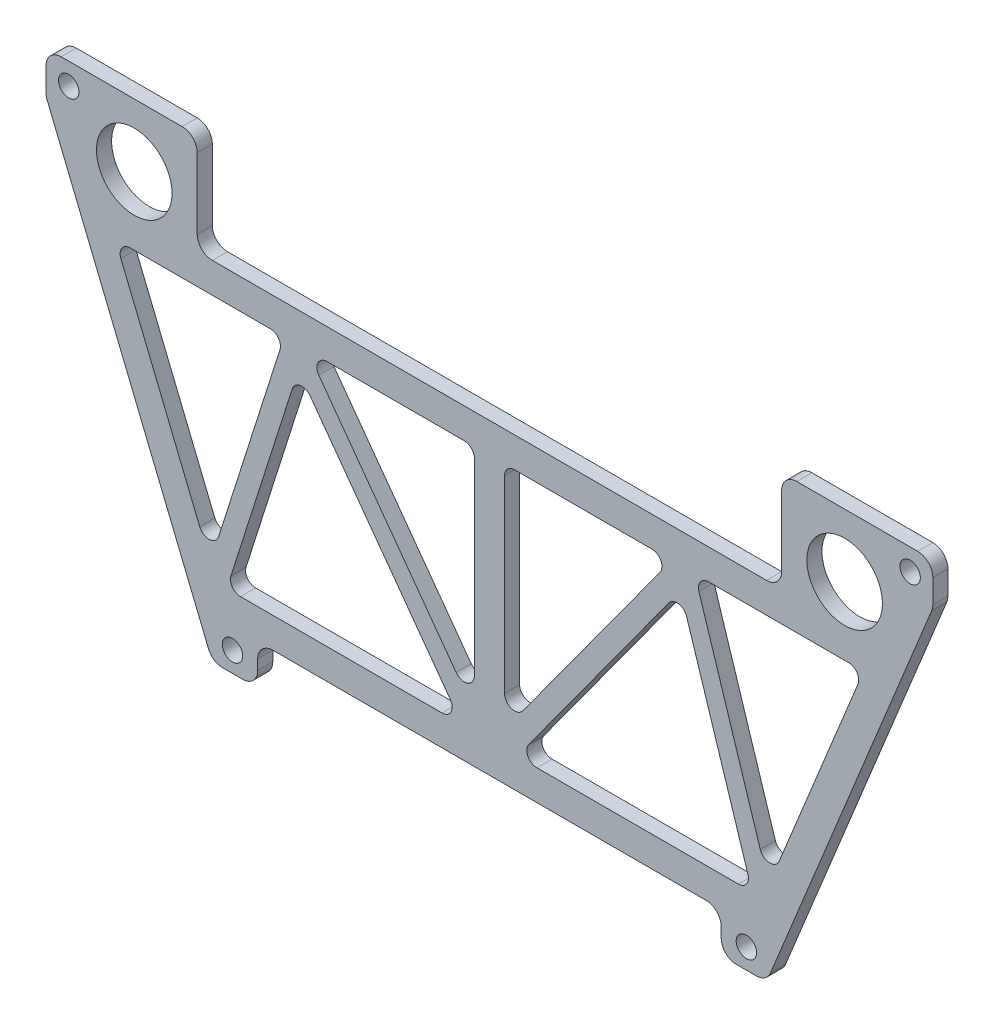
SolidWorks part; units mm, degrees
material "Thornel Mat VMA"
ref_plane "前视基准面" through (0, 0, 0) normal (0, 0, 1) x (1, 0, 0)
ref_plane "上视基准面" through (0, 0, 0) normal (0, 1, 0) x (1, 0, 0)
ref_plane "右视基准面" through (0, 0, 0) normal (1, 0, 0) x (0, 0, -1)
other "Configuration Table"
sketch "草图1" plane through (0, 0, 0) normal (0, 0, 1) x (1, 0, 0)
  line L1 (-88, -44.5) -> (88, -44.5)
  line L2 (-88, -44.5) -> (-88, 44.5)
  line L3 (-88, 44.5) -> (88, 44.5)
  line L4 (88, -44.5) -> (88, 44.5)
  line L5 (-88, -44.5) -> (88, 44.5) construction
  line L6 (-88, 44.5) -> (88, -44.5) construction
  point P0 (0, 0)
  dimension "D1" = 176
  dimension "D2" = 89
extrude "凸台-拉伸1" add sketch "草图1" along normal blind 3
sketch "草图2" plane through (0, 0, 0) normal (0, 0, -1) x (-1, 0, 0)
  circle A0 centre (-83.5, 40.2) radius 2.025 construction
  circle A1 centre (-83.5, 40.2) radius 2.025
  circle A2 centre (83.5, 40.2) radius 2.025 construction
  circle A3 centre (83.5, 40.2) radius 2.025
  circle A4 centre (51, -40.5) radius 2.025 construction
  circle A5 centre (-51, -40.5) radius 2.025 construction
  circle A6 centre (51, -40.5) radius 2.025
  circle A7 centre (-51, -40.5) radius 2.025
extrude "切除-拉伸1" cut sketch "草图2" against normal blind 4
sketch "草图3" plane through (0, 0, 0) normal (0, 0, -1) x (-1, 0, 0)
  line L1 (88, -44.5) -> (88, 36.2)
  line L2 (55, -44.5) -> (88, -44.5)
  line L5 (-88, 36.2) -> (-55, -44.5)
  line L6 (-88, -44.5) -> (-88, 44.5) construction
  line L7 (88, -44.5) -> (-88, -44.5) construction
  line L8 (-55, -44.5) -> (-88, -44.5)
  line L9 (-88, -44.5) -> (-88, 36.2)
  line L10 (0, 0) -> (0, 44.5) construction
  line L11 (-88, 44.5) -> (88, 44.5) construction
  line L12 (88, 36.2) -> (55, -44.5)
  circle A0 centre (-83.5, 40.2) radius 2.025 construction
  circle A1 centre (-51, -40.5) radius 2.025 construction
  dimension "D1" = 4
  dimension "D2" = 4
extrude "切除-拉伸2" cut sketch "草图3" against normal blind 4
sketch "草图4" plane through (0, 0, 0) normal (0, 0, -1) x (-1, 0, 0)
  line L0 (-88, 44.5) -> (88, 44.5) construction
  line L1 (-58, 24.5) -> (58, 24.5)
  line L2 (-58, 24.5) -> (-58, 64.5)
  line L3 (-58, 64.5) -> (58, 64.5)
  line L4 (58, 24.5) -> (58, 64.5)
  line L5 (-58, 24.5) -> (58, 64.5) construction
  line L6 (-58, 64.5) -> (58, 24.5) construction
  line L7 (-88, 36.2) -> (-88, 44.5) construction
  point P0 (0, 44.5)
  dimension "D1" = 30
  dimension "D2" = 20
extrude "切除-拉伸3" cut sketch "草图4" against normal blind 4
sketch "草图5" plane through (0, 0, 0) normal (0, 0, -1) x (-1, 0, 0)
  line L0 (55, -44.5) -> (-55, -44.5) construction
  line L1 (-46, -52.5) -> (46, -52.5)
  line L2 (-46, -52.5) -> (-46, -36.5)
  line L3 (-46, -36.5) -> (46, -36.5)
  line L4 (46, -52.5) -> (46, -36.5)
  line L5 (-46, -52.5) -> (46, -36.5) construction
  line L6 (-46, -36.5) -> (46, -52.5) construction
  circle A0 centre (51, -40.5) radius 2.025 construction
  point P0 (0, -44.5)
  dimension "D1" = 8
  dimension "D2" = 5
extrude "切除-拉伸4" cut sketch "草图5" against normal blind 4
sketch "草图6" plane through (0, 0, 0) normal (0, 0, -1) x (-1, 0, 0)
  line L0 (-74.2798, 18.5) -> (-54.2426, -30.5)
  line L1 (-54.2426, -30.5) -> (54.2426, -30.5)
  line L2 (54.2426, -30.5) -> (74.2798, 18.5)
  line L3 (74.2798, 18.5) -> (-74.2798, 18.5)
  line L4 (-58, 24.5) -> (58, 24.5) construction
  line L5 (-55, -44.5) -> (-88, 36.2) construction
  line L7 (88, 36.2) -> (55, -44.5) construction
  line L8 (46, -36.5) -> (-46, -36.5) construction
  line L9 (0, 18.5) -> (0, -30.5) construction
  line L10 (-3, 18.5) -> (-3, -30.5)
  line L11 (3, 18.5) -> (3, -30.5)
  dimension "D1" = 6
  dimension "D2" = 6
  dimension "D3" = 6
  dimension "D4" = 6
  dimension "D5" = 3
  dimension "D6" = 3
extrude "切除-拉伸5" cut sketch "草图6" against normal blind 24 contours L10 L3 L0 L1 | L3 L11 L1 L2
sketch "草图7" plane through (0, 0, 0) normal (0, 0, -1) x (-1, 0, 0)
  line L0 (-54.2426, -30.5) -> (-38.6399, 18.5) construction
  line L1 (-3, 18.5) -> (-74.2798, 18.5) construction
  line L2 (-38.6399, 18.5) -> (-3, -30.5) construction
  line L3 (3, -30.5) -> (38.6399, 18.5) construction
  line L4 (74.2798, 18.5) -> (3, 18.5) construction
  line L5 (38.6399, 18.5) -> (54.2426, -30.5) construction
  line L6 (-52.3369, -31.1068) -> (-37.9331, 14.1281)
  line L7 (-37.9331, 14.1281) -> (-4.6174, -31.6764)
  line L8 (4.6174, -31.6764) -> (37.9331, 14.1281)
  line L9 (37.9331, 14.1281) -> (52.3369, -31.1068)
  line L10 (-56.1484, -29.8932) -> (-39.3467, 22.8719)
  line L11 (-39.3467, 22.8719) -> (-1.3826, -29.3236)
  line L12 (1.3826, -29.3236) -> (39.3467, 22.8719)
  line L13 (39.3467, 22.8719) -> (56.1484, -29.8932)
  arc A0 (-52.3369, -31.1068) -> (-56.1484, -29.8932) centre (-54.2426, -30.5) cw
  arc A1 (-4.6174, -31.6764) -> (-1.3826, -29.3236) centre (-3, -30.5) ccw
  arc A2 (4.6174, -31.6764) -> (1.3826, -29.3236) centre (3, -30.5) cw
  arc A3 (52.3369, -31.1068) -> (56.1484, -29.8932) centre (54.2426, -30.5) ccw
  dimension "D1" = 2
  dimension "D2" = 2
extrude "凸台-拉伸2" add sketch "草图7" against normal up to surface (3 mm away) up to face at (48.975, -40.5, 3)
fillet "圆角1" radius 2 18 edges at (37.9331, 14.1281, 1.5) (52.1437, -30.5, 1.5) (5.4731, -30.5, 1.5) (3, 18.5, 1.5) (36.1668, 18.5, 1.5) (3, -27.0999, 1.5) (74.2798, 18.5, 1.5) (55.4227, -27.6142, 1.5) (40.7389, 18.5, 1.5) (-37.9331, 14.1281, 1.5) (-5.4731, -30.5, 1.5) (-52.1437, -30.5, 1.5) (-55.4227, -27.6142, 1.5) (-3, 18.5, 1.5) (-3, -27.0999, 1.5) (-36.1668, 18.5, 1.5) (-40.7389, 18.5, 1.5) (-74.2798, 18.5, 1.5)
fillet "圆角2" radius 3 14 edges at (-55, -44.5, 1.5) (-88, 36.2, 1.5) (-88, 44.5, 1.5) (58, 24.5, 1.5) (58, 44.5, 1.5) (88, 44.5, 1.5) (88, 36.2, 1.5) (55, -44.5, 1.5) (46, -44.5, 1.5) (46, -36.5, 1.5) (-46, -36.5, 1.5) (-46, -44.5, 1.5) (-58, 44.5, 1.5) (-58, 24.5, 1.5)
sketch "草图8" plane through (0, 0, 3) normal (0, 0, 1) x (1, 0, 0)
  line L2 (-61, 44.5) -> (-85, 44.5) construction
  line L4 (-58, 27.5) -> (-58, 41.5) construction
  line L6 (-71.3012, 18.5) -> (-43.4746, 18.5) construction
  line L7 (0, 0) -> (0, 41.5977) construction
  circle A0 centre (-70.5, 32) radius 7.5
  circle A1 centre (70.5, 32) radius 7.5
  dimension "D1" = 5
  dimension "D2" = 5
  dimension "D3" = 6
extrude "切除-拉伸6" cut sketch "草图8" against normal up to surface (3 mm away) up to face at (-13.9742, 4.2239, 0)
equation "\"D2@草图6\"=\"D1@草图6\""
equation "\"D3@草图6\"=\"D1@草图6\""
equation "\"D4@草图6\"=\"D1@草图6\""
